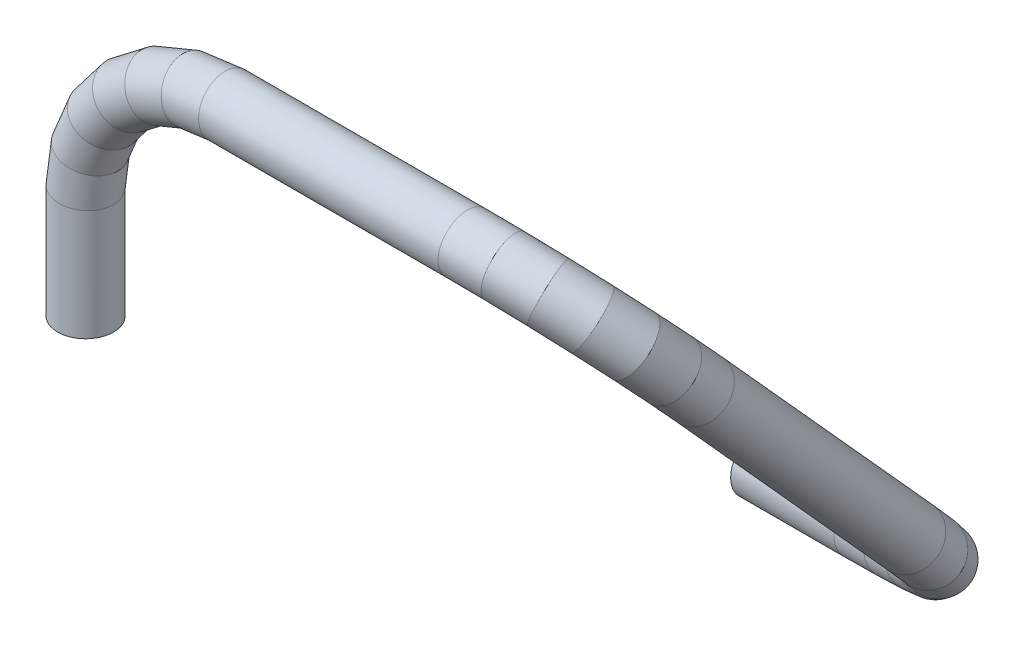
SolidWorks part; units mm, degrees
ref_plane "Front Plane" through (0, 0, 0) normal (0, 0, 1) x (1, 0, 0)
ref_plane "Top Plane" through (0, 0, 0) normal (0, 1, 0) x (1, 0, 0)
ref_plane "Right Plane" through (0, 0, 0) normal (1, 0, 0) x (0, 0, -1)
sketch3d "Path"
  line L0 (66.7, 56.8867, -67.7949) -> (84.5, 56.8867, -67.7949)
  line L1 (84.5, 56.8867, -67.7949) -> (90.7117, 57.4938, -67.247)
  line L2 (90.7117, 57.4938, -67.247) -> (96.5, 59.2736, -65.6406)
  line L3 (96.5, 59.2736, -65.6406) -> (101.4706, 62.105, -63.0851)
  line L4 (101.4706, 62.105, -63.0851) -> (105.2846, 65.7948, -59.7547)
  line L5 (105.2846, 65.7948, -59.7547) -> (107.6822, 70.0918, -55.8764)
  line L6 (107.6822, 70.0918, -55.8764) -> (108.5, 74.703, -51.7145)
  line L7 (108.5, 74.703, -51.7145) -> (108.5, 114.1837, -16.0804)
  line L8 (108.5, 114.1837, -16.0804) -> (107.6822, 118.7949, -11.9185)
  line L9 (107.6822, 118.7949, -11.9185) -> (105.2846, 123.0919, -8.0402)
  line L10 (105.2846, 123.0919, -8.0402) -> (101.4706, 126.7817, -4.7098)
  line L11 (101.4706, 126.7817, -4.7098) -> (96.5, 129.6131, -2.1544)
  line L12 (96.5, 129.6131, -2.1544) -> (90.7117, 131.3929, -0.5479)
  line L13 (90.7117, 131.3929, -0.5479) -> (84.5, 132, 0)
  line L14 (84.5, 132, 0) -> (44, 132, 0)
  line L15 (44, 132, 0) -> (37.7883, 131.1822, 0)
  line L16 (37.7883, 131.1822, 0) -> (32, 128.7846, 0)
  line L17 (32, 128.7846, 0) -> (27.0294, 124.9706, 0)
  line L18 (27.0294, 124.9706, 0) -> (23.2154, 120, 0)
  line L19 (23.2154, 120, 0) -> (20.8178, 114.2117, 0)
  line L20 (20.8178, 114.2117, 0) -> (20, 108, 0)
  line L21 (20, 108, 0) -> (20, 88.9, 0)
ref_plane "Start Plane" through (66.7, 0, 0) normal (1, 0, 0) x (0, 0, -1)
sketch "Profile" plane through (66.7, 0, 0) normal (1, 0, 0) x (0, 0, -1)
  circle A0 centre (67.7949, 56.8867) radius 4.7625
  circle A1 centre (67.7949, 56.8867) radius 3.8735
sweep "Tube" add profiles "Profile" path "Path"
